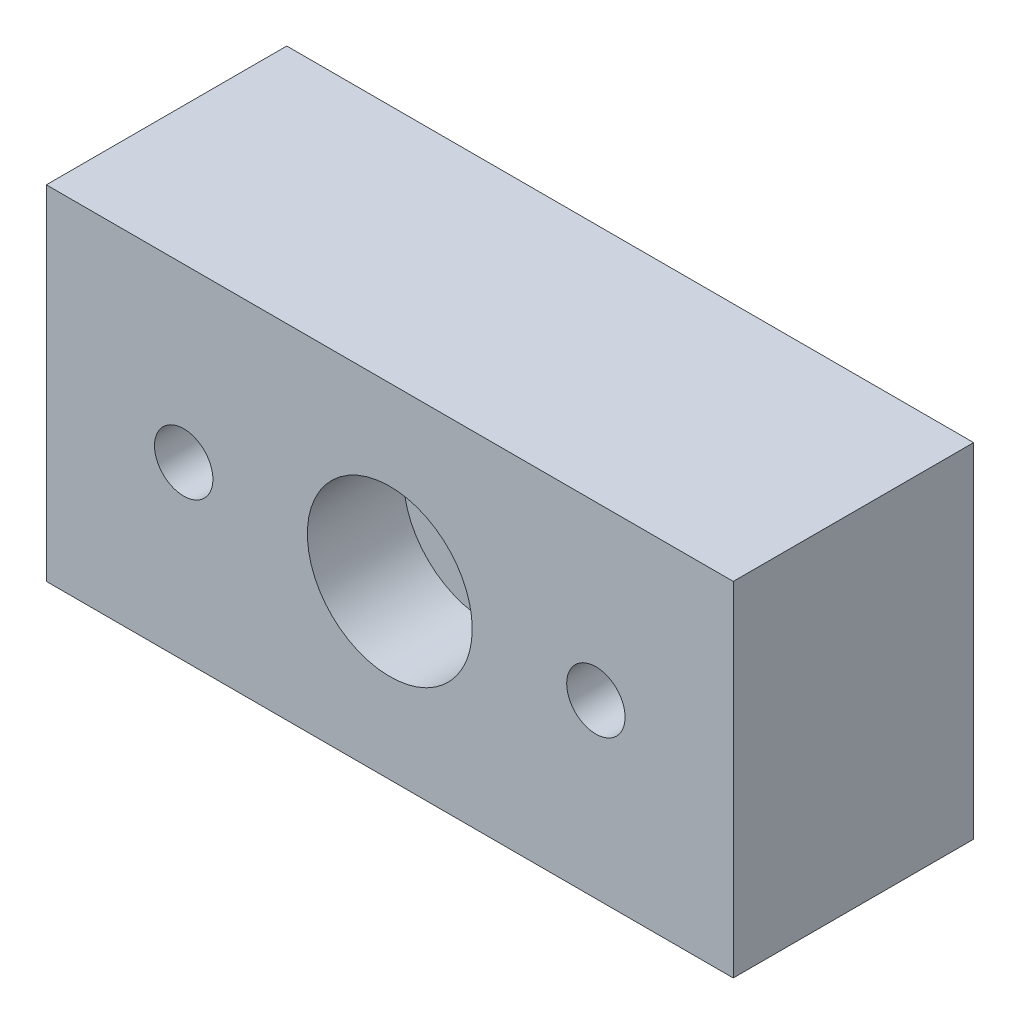
SolidWorks part; units mm, degrees
ref_plane "前视基准面" through (0, 0, 0) normal (0, 0, 1) x (1, 0, 0)
ref_plane "上视基准面" through (0, 0, 0) normal (0, 1, 0) x (1, 0, 0)
ref_plane "右视基准面" through (0, 0, 0) normal (1, 0, 0) x (0, 0, -1)
other "Configuration Table"
sketch "草图1" plane through (0, 0, 0) normal (0, 0, 1) x (1, 0, 0)
  line L1 (-50, -25) -> (50, -25)
  line L2 (-50, -25) -> (-50, 25)
  line L3 (-50, 25) -> (50, 25)
  line L4 (50, -25) -> (50, 25)
  line L5 (-50, -25) -> (50, 25) construction
  line L6 (-50, 25) -> (50, -25) construction
  point P0 (0, 0)
  dimension "D1" = 100
  dimension "D2" = 50
extrude "凸台-拉伸1" add sketch "草图1" along normal blind 35
sketch "草图2" plane through (0, 0, 35) normal (0, 0, 1) x (1, 0, 0)
  line L0 (0, 25) -> (0, -25) construction
  line L1 (50, 25) -> (-50, 25) construction
  line L2 (-50, -25) -> (50, -25) construction
  line L3 (-50, 0) -> (50, 0) construction
  line L4 (-50, 25) -> (-50, -25) construction
  line L5 (50, -25) -> (50, 25) construction
hole_wizard "Ø8.5 (8.5) 直径孔1" positions "草图3" profile "草图4" hole size "Ø8.5" standard "GB" end condition through all
sketch "草图3" plane through (0, 0, 35) normal (0, 0, 1) x (1, 0, 0)
  point P0 (0, 0)
sketch "草图4" plane through (0, 0, 35) normal (1, 0, 0) x (0, -1, 0)
  line L0 (0, 0) -> (0, 35)
  line L1 (0, 35) -> (4.25, 35)
  line L2 (4.25, 35) -> (4.25, 0)
  line L5 (4.25, 0) -> (0, 0)
  line L11 (0, -6.35) -> (0, 107.95) construction
  dimension "通孔孔直径" = 8.5
  dimension "通孔孔深度" = 35
hole_wizard "孔1" positions "草图7" profile "草图8" legacy
sketch "草图7" plane through (0, 0, 35) normal (0, 0, 1) x (1, 0, 0)
  point P0 (0, 0)
sketch "草图8" plane through (0, 0, 35) normal (1, 0, 0) x (0, -1, 0)
  line L0 (0, 0) -> (0, 14)
  line L1 (0, 14) -> (12, 14)
  line L2 (12, 14) -> (12, 0)
  line L3 (12, 0) -> (0, 0)
  line L4 (0, 110) -> (0, -10) construction
  dimension "直径" = 24
  dimension "深度" = 14
ref_plane "基准面1" through (0, 0, -10) normal (0, 0, -1) x (-1, 0, 0)
ref_plane "基准面2" through (0, 0, 0) normal (-1, 0, 0) x (0, 0, 1)
hole_wizard "孔2" positions "草图20" profile "草图21" legacy end condition through all
sketch "草图20" plane through (0, 0, 0) normal (0, 0, -1) x (-1, 0, 0)
  line L0 (50, 0) -> (-50, 0) construction
  point P0 (30, 0)
sketch "草图21" plane through (-30, 0, 0) normal (1, 0, 0) x (0, 1, 0)
  line L0 (0, 0) -> (0, 35)
  line L1 (0, 35) -> (4.25, 35)
  line L2 (4.25, 35) -> (4.25, 0)
  line L3 (4.25, 0) -> (0, 0)
  line L4 (0, 110) -> (0, -10) construction
  dimension "直径" = 8.5
  dimension "深度" = 35
ref_plane "基准面3" through (0, 0, 0) normal (-1, 0, 0) x (0, 0, 1)
mirror "镜向1" about plane through (0, 0, 0) normal (-1, 0, 0) of "孔2"
hole_wizard "孔3" positions "草图22" profile "草图23" legacy
sketch "草图22" plane through (0, 0, 0) normal (0, 0, -1) x (-1, 0, 0)
  point P0 (30, 0)
  point P3 (-30, 0)
sketch "草图23" plane through (-30, 0, 0) normal (1, 0, 0) x (0, 1, 0)
  line L0 (0, 0) -> (0, 20)
  line L1 (0, 20) -> (8, 20)
  line L2 (8, 20) -> (8, 0)
  line L3 (8, 0) -> (0, 0)
  line L4 (0, 110) -> (0, -10) construction
  dimension "直径" = 16
  dimension "深度" = 20
ref_plane "基准面4" through (0, 0, 0) normal (-1, 0, 0) x (0, 0, 1)
hole_wizard "M3.5 螺纹孔1" positions "草图24" profile "草图25" tap size "M3.5" standard "GB"
sketch "草图24" plane through (0, 0, 0) normal (0, 0, -1) x (-1, 0, 0)
  point P0 (21.077, -8.0237)
  point P3 (38.0237, -8.923)
  point P6 (38.923, 8.0237)
  point P9 (21.9763, 8.923)
  point P12 (-21.077, -8.0237)
  point P15 (-38.0237, -8.923)
  point P18 (-38.923, 8.0237)
  point P21 (-21.9763, 8.923)
sketch "草图25" plane through (-21.077, -8.0237, 0) normal (1, 0, 0) x (0, 1, 0)
  line L0 (0, 0) -> (0, 10.8712)
  line L1 (0, 10.8712) -> (1.45, 10)
  line L2 (1.45, 10) -> (1.45, 0.325)
  line L3 (1.45, 0.325) -> (1.775, 0)
  line L5 (1.775, 0) -> (0, 0)
  line L6 (-1.45, 0.325) -> (-1.775, 0) construction
  line L10 (0, 10.8712) -> (-1.45, 10) construction
  line L11 (0, -6.35) -> (0, 107.95) construction
  dimension "螺纹孔钻头直径" = 2.9
  dimension "螺纹孔钻头深度" = 10
  dimension "近端锥形沉头孔直径" = 3.55
  dimension "近端锥形沉头孔角度" = 90
  dimension "导头角度" = 118
cosmetic thread "孔螺蚊线13" parameters "D1"=7, "D2"=3.5
cosmetic thread "孔螺蚊线14" parameters "D1"=7, "D2"=3.5
cosmetic thread "孔螺蚊线15" parameters "D1"=7, "D2"=3.5
cosmetic thread "孔螺蚊线16" parameters "D1"=7, "D2"=3.5
cosmetic thread "孔螺蚊线17" parameters "D1"=7, "D2"=3.5
cosmetic thread "孔螺蚊线18" parameters "D1"=7, "D2"=3.5
cosmetic thread "孔螺蚊线19" parameters "D1"=7, "D2"=3.5
cosmetic thread "孔螺蚊线20" parameters "D1"=7, "D2"=3.5
